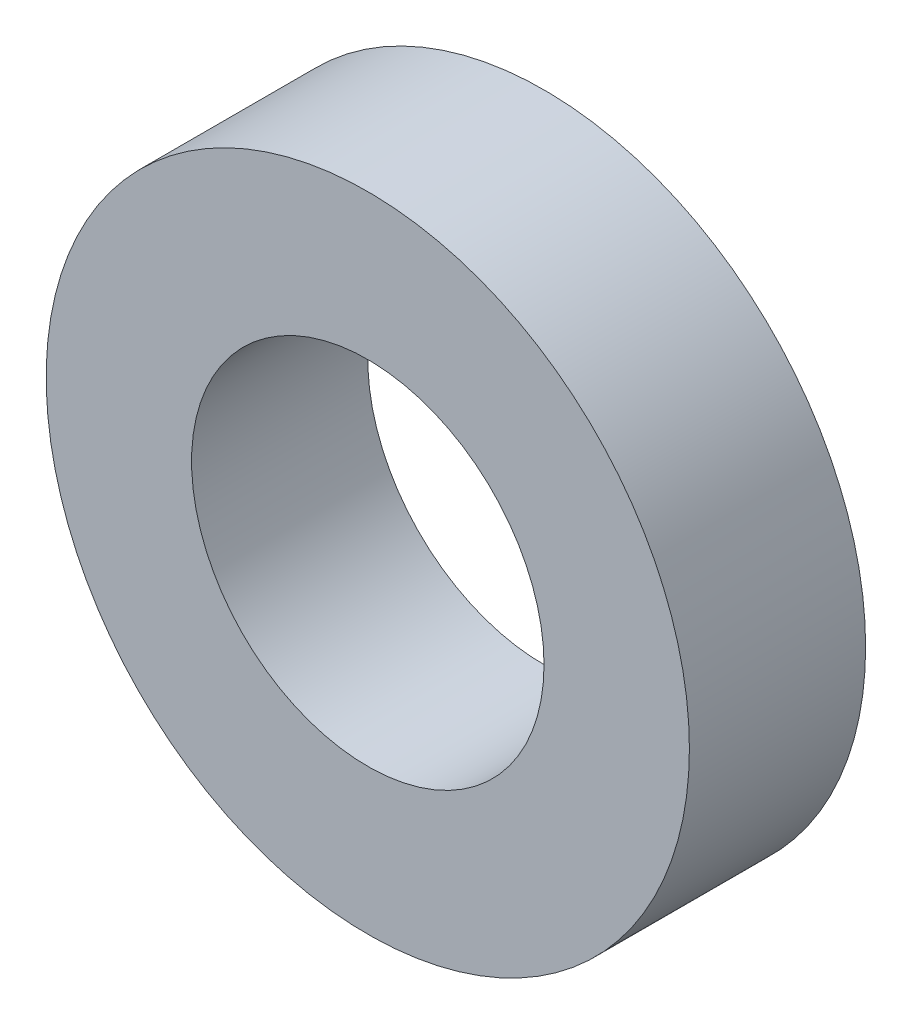
SolidWorks part; units mm, degrees
ref_plane "Front Plane" through (0, 0, 0) normal (0, 0, 1) x (1, 0, 0)
ref_plane "Top Plane" through (0, 0, 0) normal (0, 1, 0) x (1, 0, 0)
ref_plane "Right Plane" through (0, 0, 0) normal (1, 0, 0) x (0, 0, -1)
sketch "Sketch1" plane through (0, 34.7031, 0) normal (0, 0, 1) x (1, 0, 0)
  circle A3 centre (192.4205, 258.6782) radius 2
  circle A4 centre (192.4205, 258.6782) radius 3.65
  dimension "D4" = 4
  dimension "D1" = 7.3
extrude "Boss-Extrude1" add sketch "Sketch1" along normal blind 2
